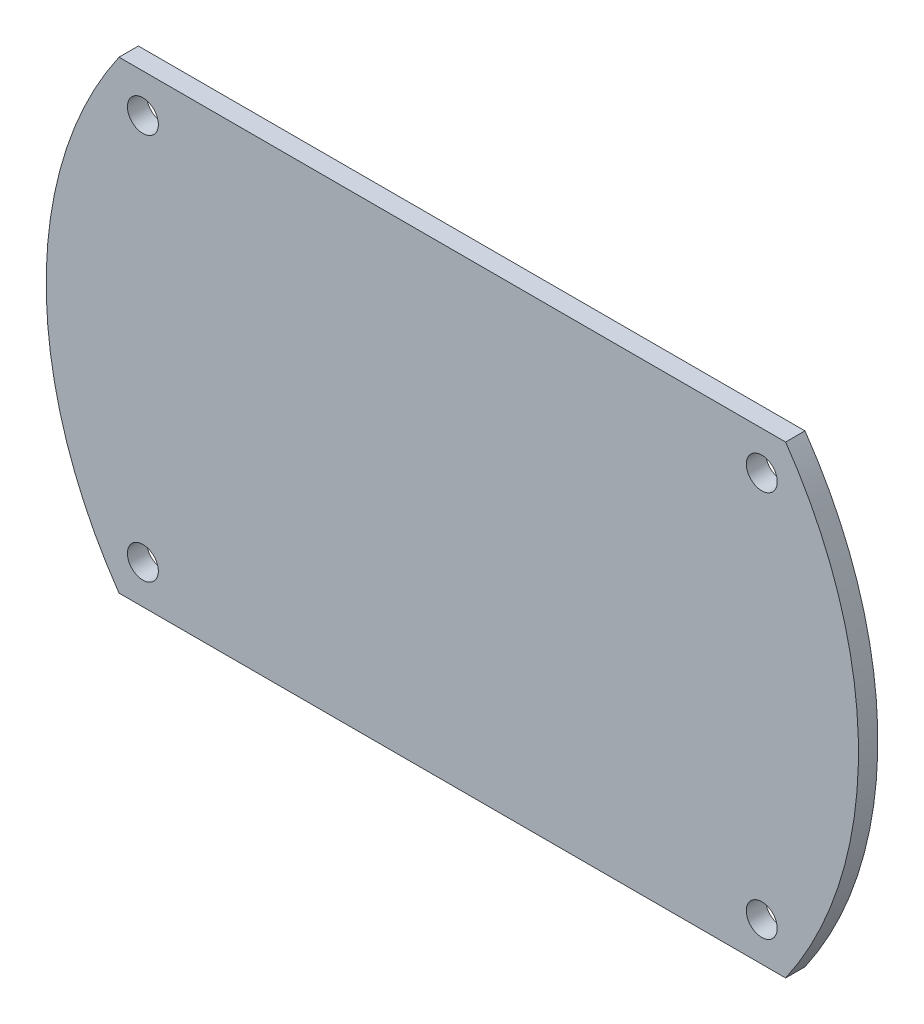
SolidWorks part; units mm, degrees
material "Polyéthylène réticulé"
ref_plane "Plan de face" through (0, 0, 0) normal (0, 0, 1) x (1, 0, 0)
ref_plane "Plan de dessus" through (0, 0, 0) normal (0, 1, 0) x (1, 0, 0)
ref_plane "Plan de droite" through (0, 0, 0) normal (1, 0, 0) x (0, 0, -1)
sketch "Esquisse1" plane through (0, 0, 0) normal (0, 0, 1) x (1, 0, 0)
  line L0 (0, 113.8712) -> (0, -130.9268) construction
  line L11 (-121.3457, 0) -> (123.2263, 0) construction
  circle A0 centre (0, 0) radius 105
  circle A1 centre (-80, 50) radius 4
  circle A2 centre (80, 50) radius 4
  circle A3 centre (80, -50) radius 4
  circle A4 centre (-80, -50) radius 4
  point P3 (-80, 0)
  dimension "D1" = 210
  dimension "D5" = 8
  dimension "D3" = 80
  dimension "D6" = 80
  dimension "D7" = 50
extrude "Boss.-Extru.1" add sketch "Esquisse1" along normal blind 5
sketch "Esquisse2" plane through (0, 0, 5) normal (0, 0, 1) x (1, 0, 0)
  line L0 (186.3345, 0) -> (-169.5267, 0) construction
  line L1 (125, 110) -> (-125, 110)
  line L2 (125, 110) -> (125, 60)
  line L3 (125, 60) -> (-125, 60)
  line L4 (-125, 110) -> (-125, 60)
  line L5 (-125, -110) -> (-125, -60)
  line L6 (125, -60) -> (-125, -60)
  line L7 (125, -110) -> (125, -60)
  line L8 (125, -110) -> (-125, -110)
  point P4 (0, 60)
  dimension "D1" = 60
  dimension "D2" = 50
  dimension "D3" = 250
extrude "Enlèv. mat.-Extru.1" cut sketch "Esquisse2" against normal through all
